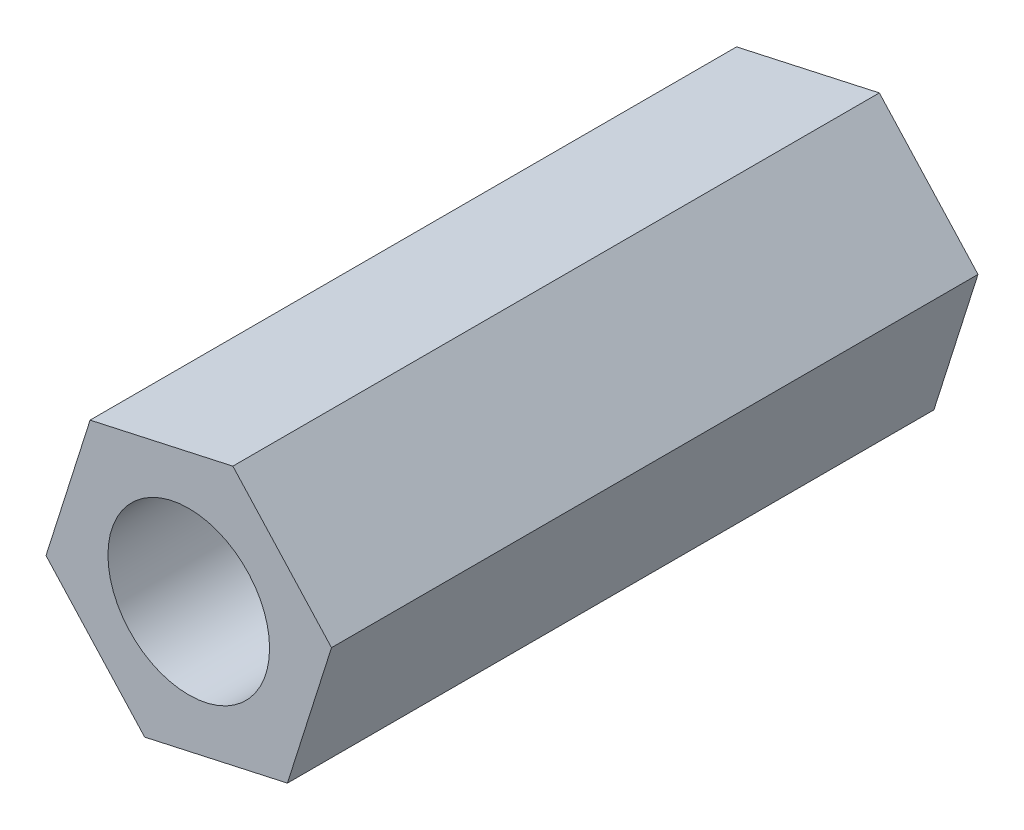
SolidWorks part; units mm, degrees
ref_plane "前视基准面" through (0, 0, 0) normal (0, 0, 1) x (1, 0, 0)
ref_plane "上视基准面" through (0, 0, 0) normal (0, 1, 0) x (1, 0, 0)
ref_plane "右视基准面" through (0, 0, 0) normal (1, 0, 0) x (0, 0, -1)
sketch "草图1" plane through (0, 0, 0) normal (0, 0, 1) x (1, 0, 0)
  line L1 (2.6498, 0.5847) -> (0.8185, 2.5871)
  line L2 (0.8185, 2.5871) -> (-1.8313, 2.0024)
  line L3 (-1.8313, 2.0024) -> (-2.6498, -0.5847)
  line L4 (-2.6498, -0.5847) -> (-0.8185, -2.5871)
  line L5 (-0.8185, -2.5871) -> (1.8313, -2.0024)
  line L6 (1.8313, -2.0024) -> (2.6498, 0.5847)
  circle A0 centre (0, 0) radius 2.35 construction
  circle A1 centre (0, 0) radius 1.5
extrude "凸台-拉伸1" add sketch "草图1" along normal blind 12
